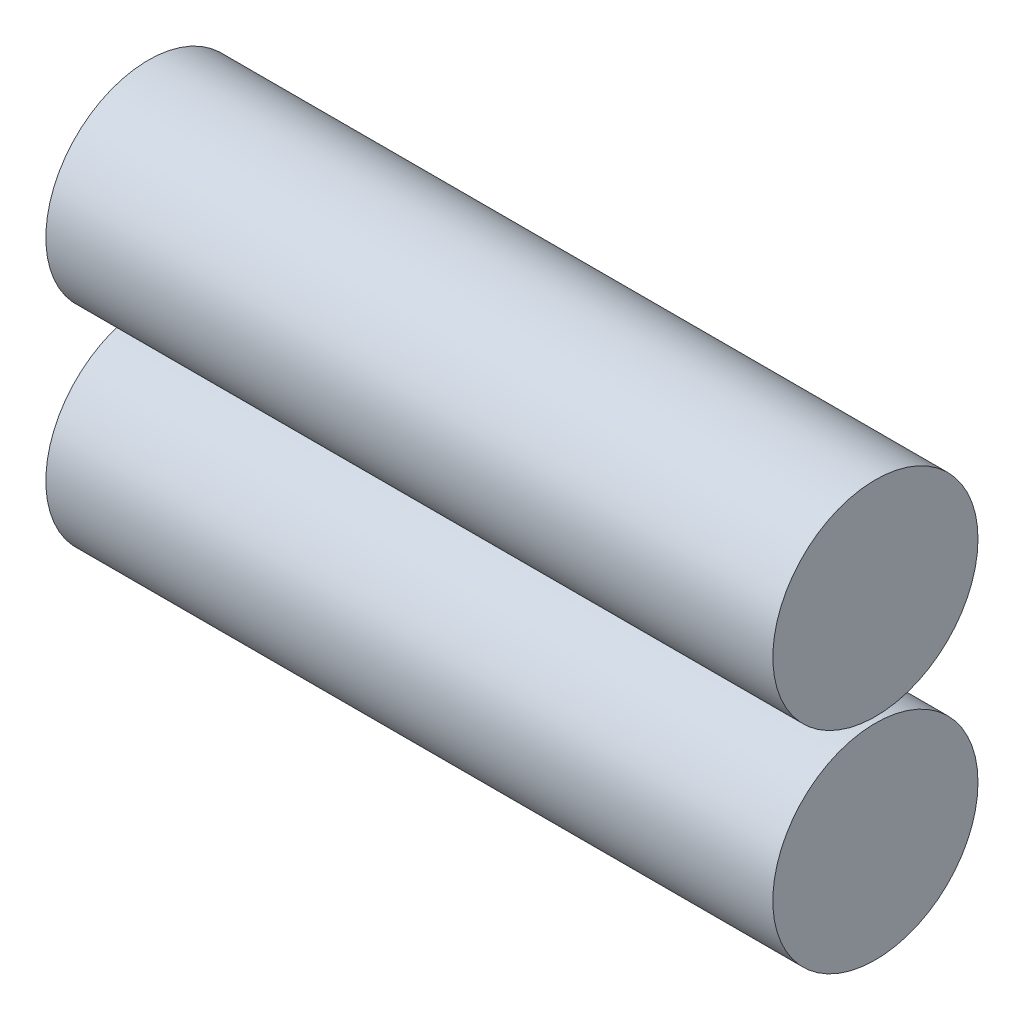
SolidWorks part; units mm, degrees
ref_plane "Front Plane" through (0, 0, 0) normal (0, 0, 1) x (1, 0, 0)
ref_plane "Top Plane" through (0, 0, 0) normal (0, 1, 0) x (1, 0, 0)
ref_plane "Right Plane" through (0, 0, 0) normal (1, 0, 0) x (0, 0, -1)
ref_plane "Plane1" through (-32.6, 0, 0) normal (1, 0, 0) x (0, 0, -1)
sketch "Sketch1" plane through (-32.6, 0, 0) normal (1, 0, 0) x (0, 0, -1)
  circle A0 centre (-14.2, -49.45) radius 9.2
extrude "Boss-Extrude1" add sketch "Sketch1" along normal blind 65.2
sketch "Sketch2" plane through (-32.6, 0, 0) normal (1, 0, 0) x (0, 0, -1)
  circle A0 centre (-14.2, -30.55) radius 9.2
extrude "Boss-Extrude2" add sketch "Sketch2" along normal blind 65.2
